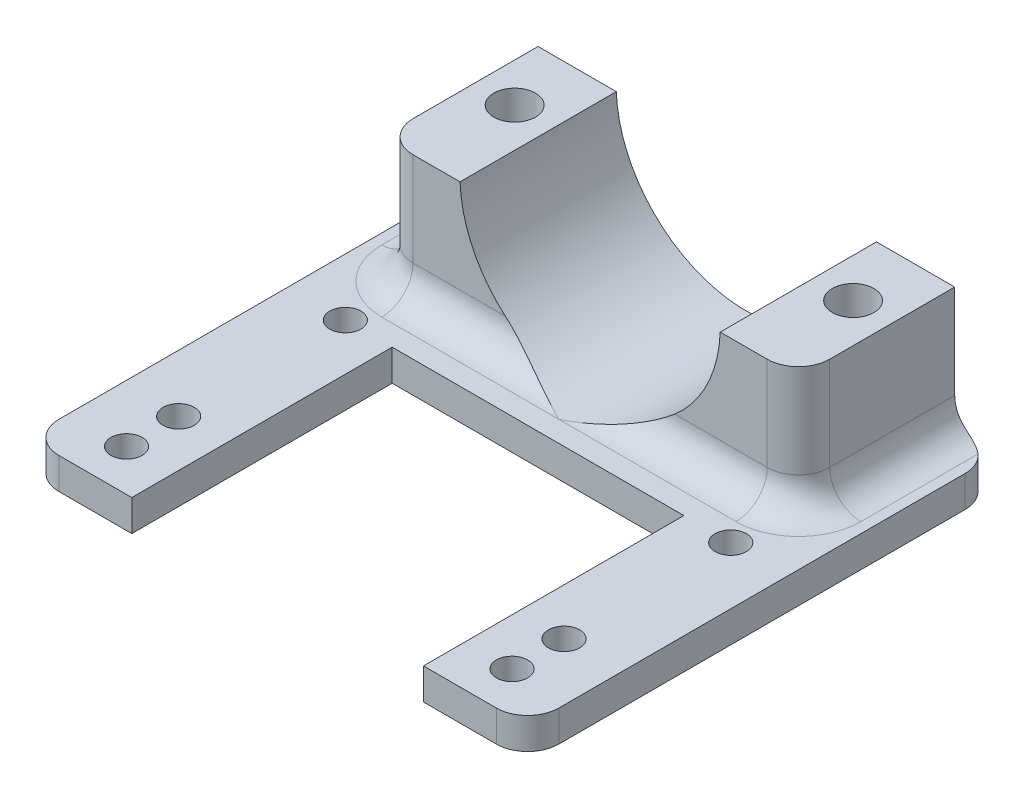
SolidWorks part; units mm, degrees
ref_plane "Front Plane" through (0, 0, 0) normal (0, 0, 1) x (1, 0, 0)
ref_plane "Top Plane" through (0, 0, 0) normal (0, 1, 0) x (1, 0, 0)
ref_plane "Right Plane" through (0, 0, 0) normal (1, 0, 0) x (0, 0, -1)
sketch "Sketch1" plane through (0, 0, 0) normal (0, 1, 0) x (1, 0, 0)
  line L0 (0, -39.2464) -> (0, 32.3227) construction
  line L1 (-21, 22.5) -> (21, 22.5)
  line L2 (-24, 19.5) -> (-24, -19.5)
  line L3 (-21, -22.5) -> (21, -22.5)
  line L4 (24, 19.5) -> (24, -19.5)
  line L5 (-24, 22.5) -> (24, -22.5) construction
  line L6 (-24, -22.5) -> (24, 22.5) construction
  line L11 (-14, 2.5) -> (14, 2.5)
  line L12 (-14, 2.5) -> (-14, -22.5)
  line L13 (-14, -22.5) -> (14, -22.5)
  line L14 (14, 2.5) -> (14, -22.5)
  line L15 (-14, 2.5) -> (14, -22.5) construction
  line L16 (-14, -22.5) -> (14, 2.5) construction
  circle A0 centre (-18.5, -18.5) radius 1.5
  circle A2 centre (-18.5, -13.5) radius 1.5
  circle A3 centre (-18.5, 2.5) radius 1.5
  circle A4 centre (18.5, 2.5) radius 1.5
  circle A5 centre (18.5, -13.5) radius 1.5
  circle A6 centre (18.5, -18.5) radius 1.5
  arc A7 (21, -22.5) -> (24, -19.5) centre (21, -19.5) ccw
  arc A8 (-24, -19.5) -> (-21, -22.5) centre (-21, -19.5) ccw
  arc A9 (21, 22.5) -> (24, 19.5) centre (21, 19.5) cw
  arc A10 (-21, 22.5) -> (-24, 19.5) centre (-21, 19.5) ccw
  point P0 (0, 0)
  point P6 (0, -10)
  dimension "D6" = 3
  dimension "D10" = 3
  dimension "D1" = 48
  dimension "D2" = 28
  dimension "D3" = 25
  dimension "D4" = 20
  dimension "D5" = 65.7951
  dimension "D7" = 18.5
  dimension "D8" = 2
  dimension "D9" = 16
extrude "Boss-Extrude1" add sketch "Sketch1" along normal blind 3 contours L11 L14 L3 L4 L1 L2 L12 A5 A0 A2 A3 A4 A6
sketch "Sketch4" plane through (0, 0, -22.5) normal (0, 0, -1) x (-1, 0, 0)
  line L0 (-24, 0) -> (-21, 0) construction
  line L1 (-20, 0) -> (20, 0)
  line L2 (-20, 0) -> (-20, 15)
  line L3 (-20, 15) -> (20, 15)
  line L4 (20, 0) -> (20, 15)
  point P6 (0, 15)
  dimension "D1" = 15
  dimension "D2" = 40
extrude "Boss-Extrude2" add sketch "Sketch4" against normal blind 15
fillet "Fillet5" radius 3 5 edges at (20, 3, -15) (-20, 3, -15) (0, 3, -7.5) (20, 9, -7.5) (-20, 9, -7.5)
sketch "Sketch5" plane through (0, 0, -22.5) normal (0, 0, -1) x (-1, 0, 0)
  line L0 (-20, 3) -> (-21, 3) construction
  circle A0 centre (0, 15.5) radius 12.5
  dimension "D1" = 25
extrude "Cut-Extrude1" cut sketch "Sketch5" against normal through all
sketch "Sketch6" plane through (0, 15, 0) normal (0, 1, 0) x (1, 0, 0)
  line L0 (-20, 22.5) -> (-12.49, 22.5) construction
  line L1 (0, 22.5) -> (0, -22.2134) construction
  line L2 (12.49, 22.5) -> (-12.49, 22.5) construction
  line L3 (-20, 10.5) -> (-20, 22.5) construction
  circle A0 centre (-16.245, 16.5) radius 2
  circle A1 centre (16.245, 16.5) radius 2
  point P5 (-16.245, 22.5)
  point P15 (-20, 16.5)
  dimension "D1" = 4
extrude "Cut-Extrude2" cut sketch "Sketch6" against normal blind 5
